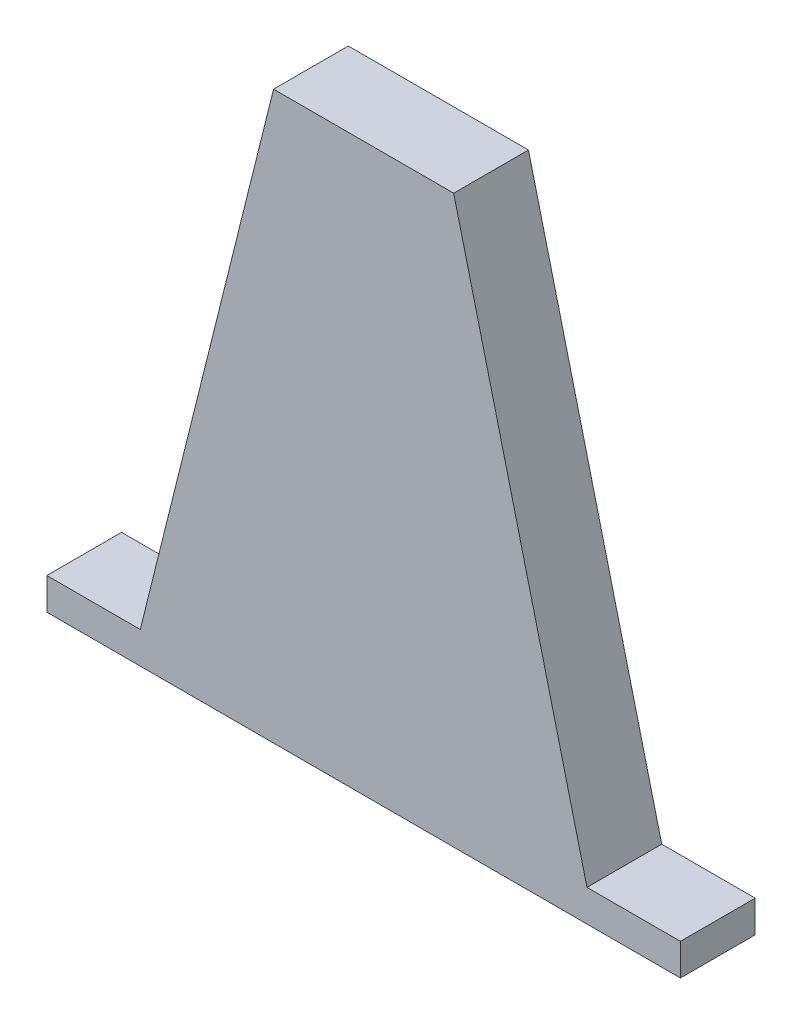
SolidWorks part; units mm, degrees
ref_plane "Front Plane" through (0, 0, 0) normal (0, 0, 1) x (1, 0, 0)
ref_plane "Top Plane" through (0, 0, 0) normal (0, 1, 0) x (1, 0, 0)
ref_plane "Right Plane" through (0, 0, 0) normal (1, 0, 0) x (0, 0, -1)
ref_plane "Plane1" through (0, -76.608, -0.0153) normal (0, -1, -0.0002) x (-1, 0, 0)
sketch "Sketch1" plane through (0, 0, 0) normal (0, 0, 1) x (1, 0, 0)
  line L0 (-85.5, -68) -> (-60.5, -68)
  line L1 (84, -68) -> (84, -76.5)
  line L2 (84, -76.5) -> (-85.5, -76.5)
  line L3 (-85.5, -76.5) -> (-85.5, -68)
  line L4 (0, 0) -> (0, -231.874) construction
  line L5 (0, 0) -> (-193.6308, 0) construction
  line L6 (-24.8461, 75) -> (-60.5, -68)
  line L7 (59, -68) -> (23.3461, 75)
  line L8 (23.3461, 75) -> (-24.8461, 75) construction
  line L9 (-24.8461, 75) -> (23.3461, 75)
  line L10 (59, -68) -> (84, -68)
  dimension "D1" = 85.5
  dimension "D2" = 8.5
  dimension "D3" = 84
  dimension "D4" = 68
  dimension "D5" = 25
  dimension "D6" = 25
  dimension "D7" = 75
  dimension "D8" = 76
  dimension "D9" = 76
extrude "Boss-Extrude1" add sketch "Sketch1" along normal blind 20
